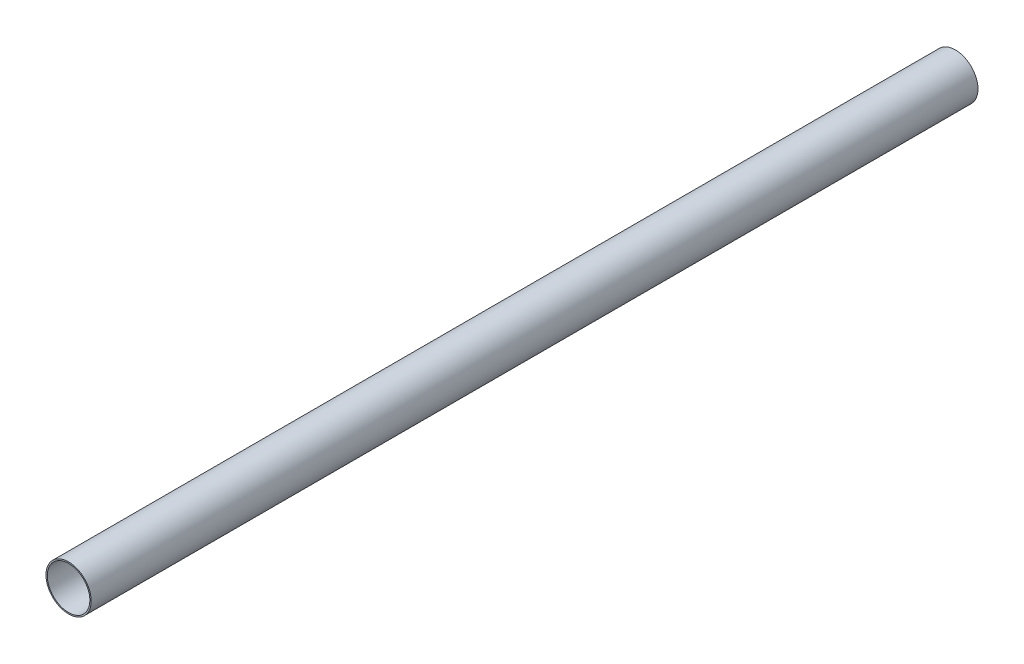
SolidWorks part; units mm, degrees
ref_plane "Спереди" through (0, 0, 0) normal (0, 0, 1) x (1, 0, 0)
ref_plane "Сверху" through (0, 0, 0) normal (0, 1, 0) x (1, 0, 0)
ref_plane "Справа" through (0, 0, 0) normal (1, 0, 0) x (0, 0, -1)
sketch "Эскиз1" plane through (0, 0, 0) normal (0, 0, 1) x (1, 0, 0)
  circle A0 centre (0, 0) radius 24
  circle A1 centre (0, 0) radius 25.5
  dimension "D1" = 48
  dimension "D2" = 51
extrude "Бобышка-Вытянуть1" add sketch "Эскиз1" along normal mid plane 1000
